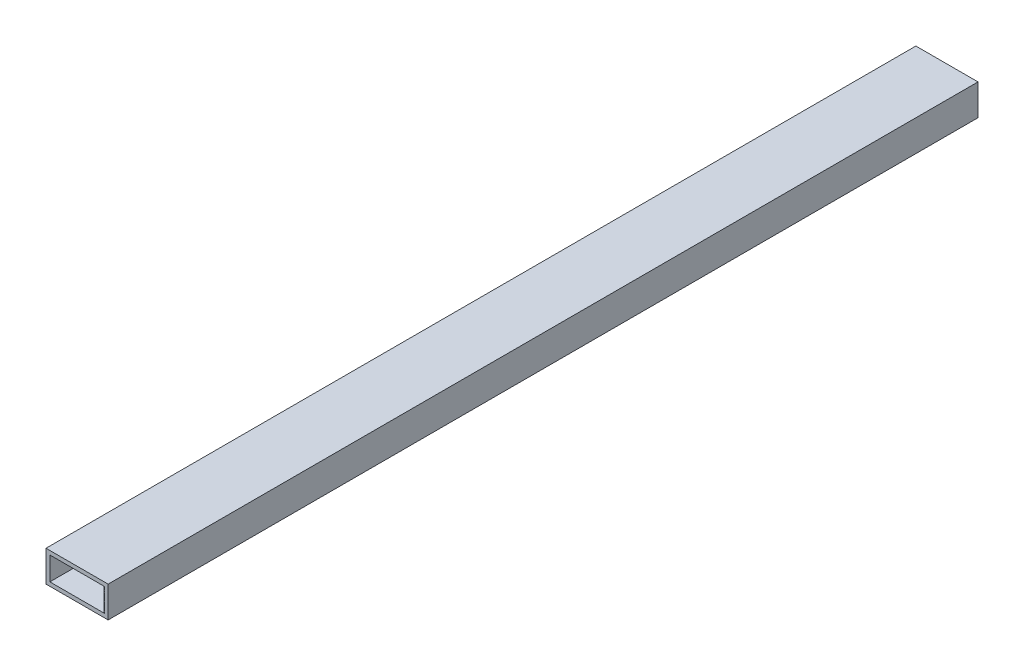
SolidWorks part; units mm, degrees
ref_plane "Front Plane" through (0, 0, 0) normal (0, 0, 1) x (1, 0, 0)
ref_plane "Top Plane" through (0, 0, 0) normal (0, 1, 0) x (1, 0, 0)
ref_plane "Right Plane" through (0, 0, 0) normal (1, 0, 0) x (0, 0, -1)
sketch "Sketch1" plane through (0, 0, 0) normal (0, 0, 1) x (1, 0, 0)
  line L1 (-25.4, 12.7) -> (25.4, 12.7)
  line L2 (-25.4, 12.7) -> (-25.4, -12.7)
  line L3 (-25.4, -12.7) -> (25.4, -12.7)
  line L4 (25.4, 12.7) -> (25.4, -12.7)
  line L5 (-25.4, 12.7) -> (25.4, -12.7) construction
  line L6 (-25.4, -12.7) -> (25.4, 12.7) construction
  point P0 (0, 0)
  dimension "D1" = 50.8
  dimension "D2" = 25.4
extrude "Boss-Extrude1" add sketch "Sketch1" along normal blind 711.2
shell "Shell1" thickness 3.175
